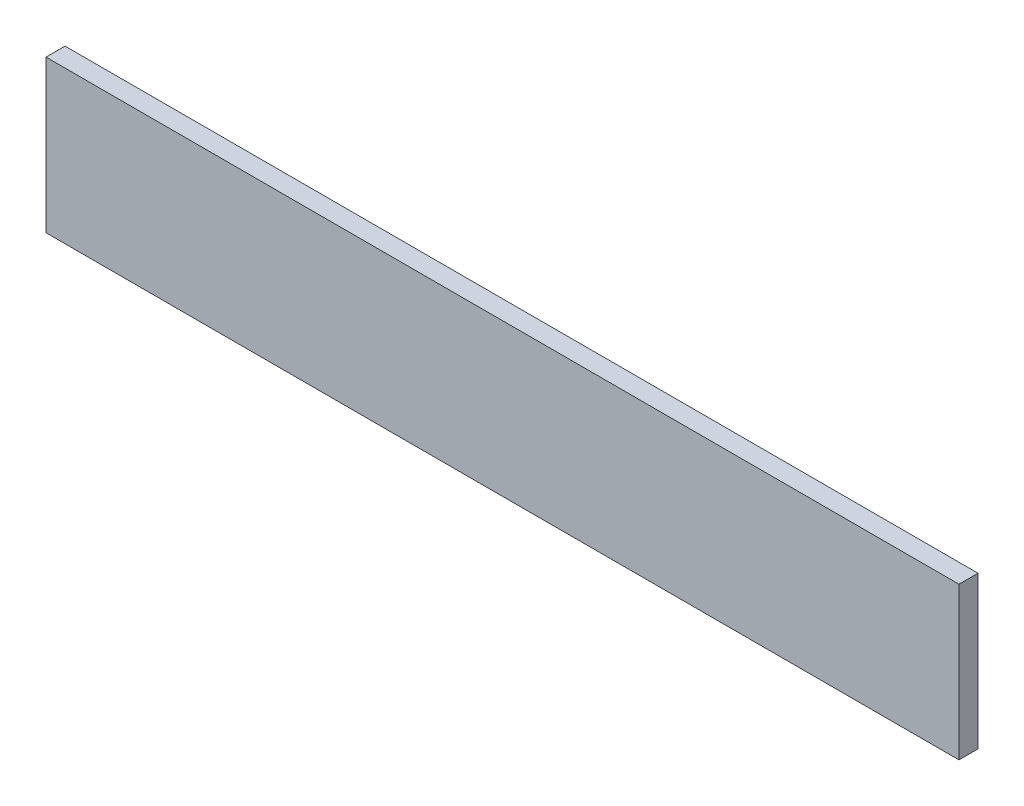
SolidWorks part; units mm, degrees
ref_plane "Front Plane" through (0, 0, 0) normal (0, 0, 1) x (1, 0, 0)
ref_plane "Top Plane" through (0, 0, 0) normal (0, 1, 0) x (1, 0, 0)
ref_plane "Right Plane" through (0, 0, 0) normal (1, 0, 0) x (0, 0, -1)
sketch "Sketch1" plane through (0, 0, 0) normal (0, 0, 1) x (1, 0, 0)
  line L1 (-240, 40) -> (240, 40)
  line L2 (-240, 40) -> (-240, -40)
  line L3 (-240, -40) -> (240, -40)
  line L4 (240, 40) -> (240, -40)
  line L5 (-240, 40) -> (240, -40) construction
  line L6 (-240, -40) -> (240, 40) construction
  point P0 (0, 0)
  point P6 (240, 0)
  dimension "D1" = 480
  dimension "D2" = 40
extrude "Boss-Extrude1" add sketch "Sketch1" along normal blind 10
